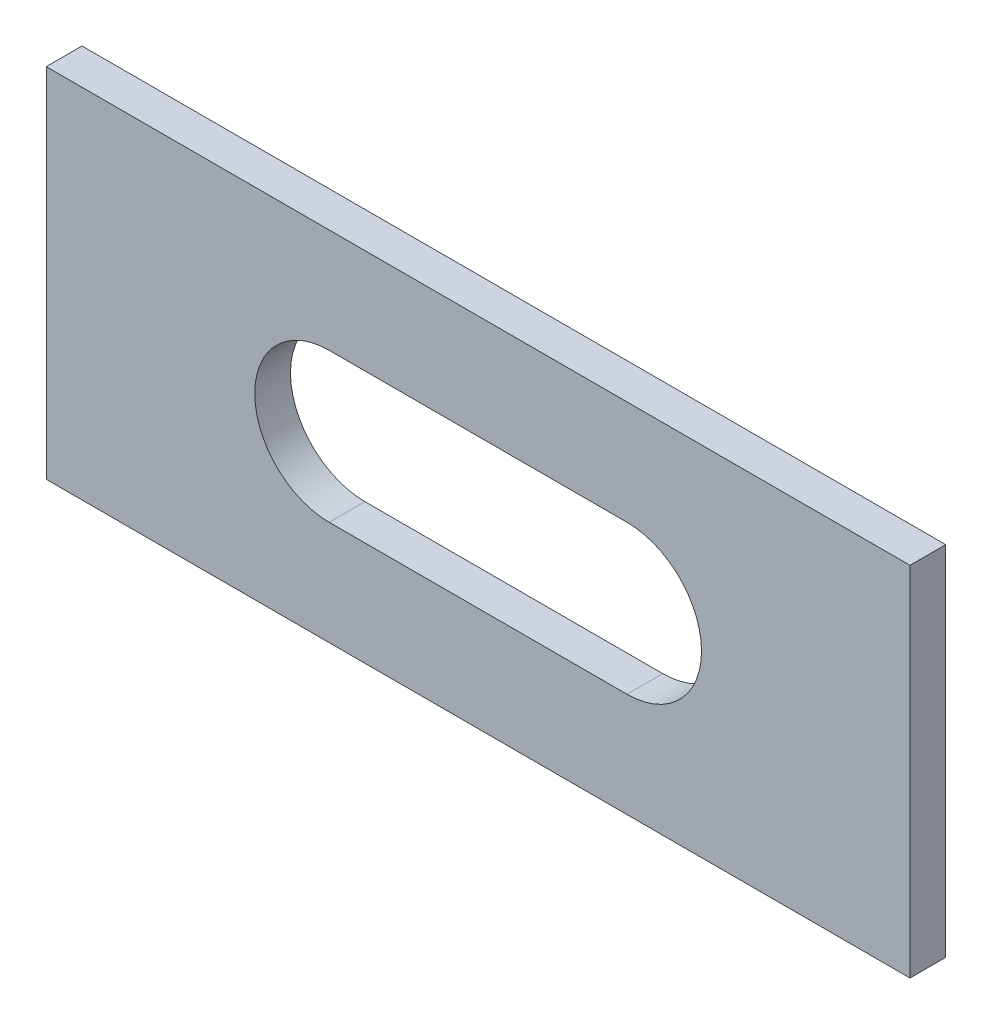
SolidWorks part; units mm, degrees
material "MDF"
ref_plane "Plano frontal" through (0, 0, 0) normal (0, 0, 1) x (1, 0, 0)
ref_plane "Plano superior" through (0, 0, 0) normal (0, 1, 0) x (1, 0, 0)
ref_plane "Plano direito" through (0, 0, 0) normal (1, 0, 0) x (0, 0, -1)
sketch "Esboço1" plane through (0, 0, 0) normal (0, 0, 1) x (1, 0, 0)
  line L0 (-25, 0) -> (25, 0) construction
  line L1 (72.5, -30) -> (-72.5, -30)
  line L2 (72.5, -30) -> (72.5, 30)
  line L3 (72.5, 30) -> (-72.5, 30)
  line L4 (-72.5, -30) -> (-72.5, 30)
  line L5 (72.5, -30) -> (-72.5, 30) construction
  line L6 (72.5, 30) -> (-72.5, -30) construction
  line L7 (-25, 12.5) -> (25, 12.5)
  line L8 (-25, -12.5) -> (25, -12.5)
  arc A0 (-25, 12.5) -> (-25, -12.5) centre (-25, 0) ccw
  arc A1 (25, -12.5) -> (25, 12.5) centre (25, 0) ccw
  point P0 (0, 0)
  point P8 (0, 0)
  dimension "D1" = 145
  dimension "D2" = 30
  dimension "D3" = 25
  dimension "D4" = 25
  dimension "D5" = 25
extrude "Ressalto-extrusão1" add sketch "Esboço1" along normal blind 6
